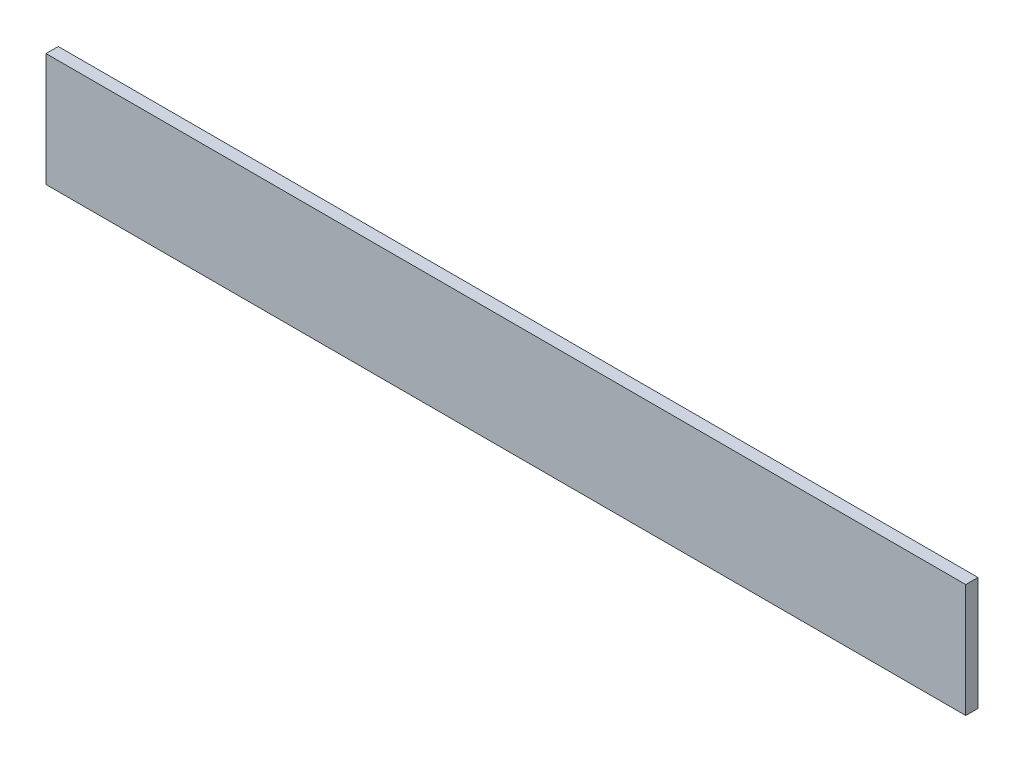
SolidWorks part; units mm, degrees
ref_plane "Front Plane" through (0, 0, 0) normal (0, 0, 1) x (1, 0, 0)
ref_plane "Top Plane" through (0, 0, 0) normal (0, 1, 0) x (1, 0, 0)
ref_plane "Right Plane" through (0, 0, 0) normal (1, 0, 0) x (0, 0, -1)
sketch "Sketch1" plane through (0, 0, 0) normal (0, 0, 1) x (1, 0, 0)
  line L1 (-150, 18.5) -> (150, 18.5)
  line L2 (-150, 18.5) -> (-150, -18.5)
  line L3 (-150, -18.5) -> (150, -18.5)
  line L4 (150, 18.5) -> (150, -18.5)
  line L5 (-150, 18.5) -> (150, -18.5) construction
  line L6 (-150, -18.5) -> (150, 18.5) construction
  point P0 (0, 0)
extrude "Boss-Extrude1" add sketch "Sketch1" along normal blind 4
